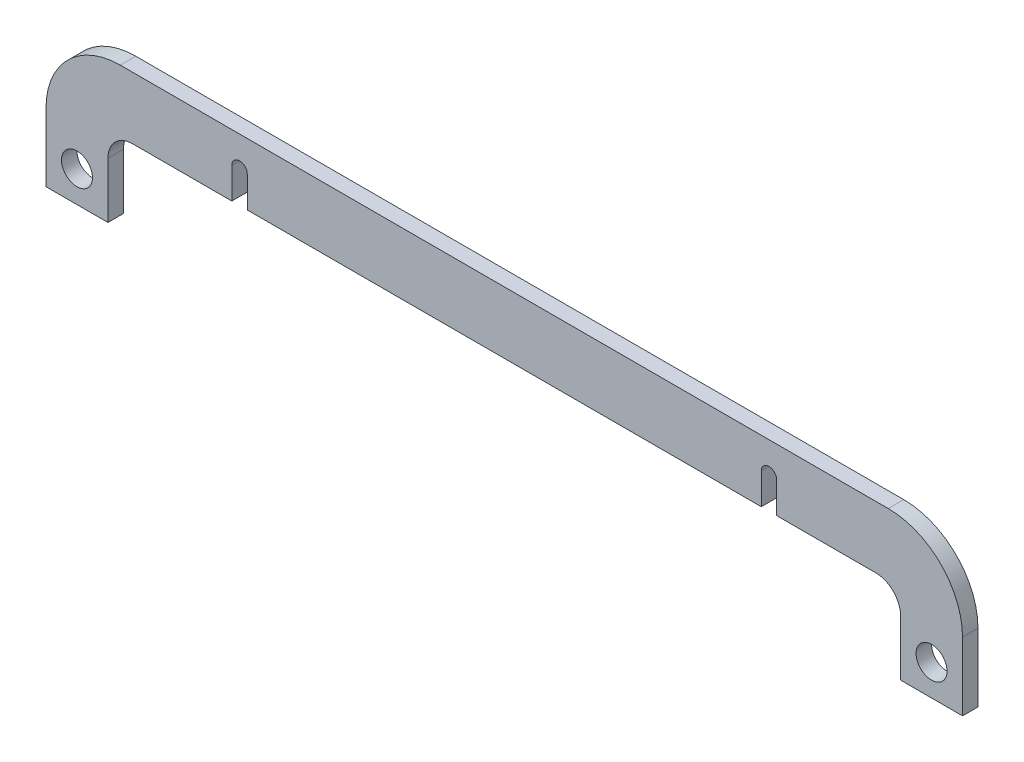
SolidWorks part; units mm, degrees
material "G10"
ref_plane "Front Plane" through (0, 0, 0) normal (0, 0, 1) x (1, 0, 0)
ref_plane "Top Plane" through (0, 0, 0) normal (0, 1, 0) x (1, 0, 0)
ref_plane "Right Plane" through (0, 0, 0) normal (1, 0, 0) x (0, 0, -1)
sketch "Sketch1" plane through (0, 0, 0) normal (0, 0, 1) x (1, 0, 0)
  line L0 (-56.9486, 20.32) -> (60.5558, 20.32) construction
  line L1 (-43.815, 23.495) -> (57.3185, 23.495) construction
  line L2 (-40.64, 20.32) -> (-40.64, 26.035)
  line L3 (-38.1, 28.575) -> (-27.94, 28.575)
  line L4 (40.64, 20.32) -> (40.64, 26.035)
  line L5 (-40.64, -28.575) -> (40.64, 28.575) construction
  line L6 (-40.64, 28.575) -> (40.64, -28.575) construction
  line L7 (-39.37, 34.925) -> (39.37, 34.925)
  line L8 (-46.99, 27.305) -> (-46.99, 20.32)
  line L9 (0, 28.575) -> (0, 15.9243) construction
  line L10 (46.99, 27.305) -> (46.99, 20.32)
  line L11 (-46.99, 34.925) -> (46.99, -34.925) construction
  line L12 (-46.99, -34.925) -> (46.99, 34.925) construction
  line L13 (-46.99, 20.32) -> (-40.64, 20.32)
  line L14 (40.64, 20.32) -> (46.99, 20.32)
  line L15 (27.94, 28.575) -> (27.94, 31.75)
  line L17 (-27.94, 28.575) -> (-27.94, 31.75)
  line L19 (-26.3525, 28.575) -> (-26.3525, 31.75)
  line L21 (26.3525, 28.575) -> (26.3525, 31.75)
  line L22 (27.94, 28.575) -> (38.1, 28.575)
  line L23 (-26.3525, 28.575) -> (26.3525, 28.575)
  circle A0 centre (-43.815, 23.495) radius 1.5875
  circle A1 centre (43.815, 23.495) radius 1.5875
  arc A2 (-26.3525, 31.75) -> (-27.94, 31.75) centre (-27.1463, 31.75) ccw
  arc A3 (27.94, 31.75) -> (26.3525, 31.75) centre (27.1463, 31.75) ccw
  arc A4 (-39.37, 34.925) -> (-46.99, 27.305) centre (-39.37, 27.305) ccw
  arc A5 (46.99, 27.305) -> (39.37, 34.925) centre (39.37, 27.305) ccw
  arc A6 (-40.64, 26.035) -> (-38.1, 28.575) centre (-38.1, 26.035) cw
  arc A7 (40.64, 26.035) -> (38.1, 28.575) centre (38.1, 26.035) ccw
extrude "Boss-Extrude1" add sketch "Sketch1" along normal blind 1.5875
